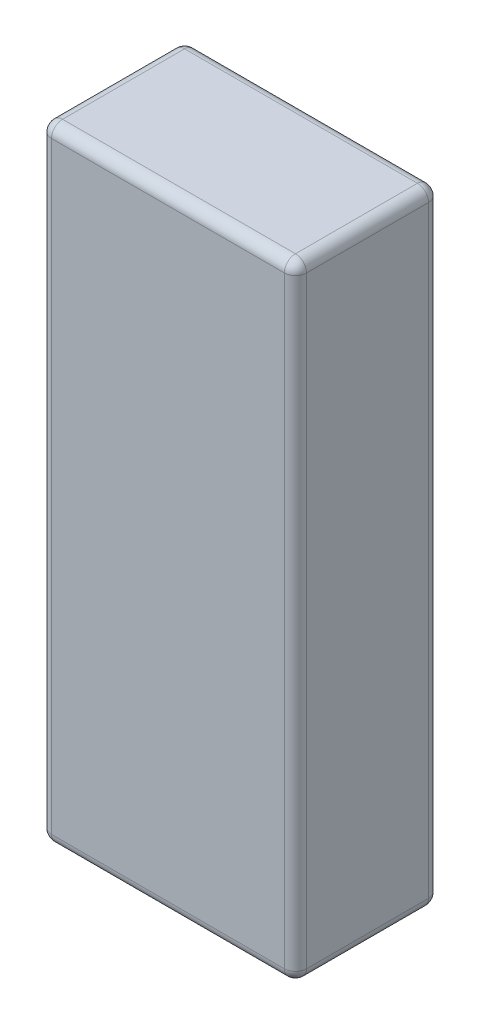
SolidWorks part; units mm, degrees
ref_plane "Front Plane" through (0, 0, 0) normal (0, 0, 1) x (1, 0, 0)
ref_plane "Top Plane" through (0, 0, 0) normal (0, 1, 0) x (1, 0, 0)
ref_plane "Right Plane" through (0, 0, 0) normal (1, 0, 0) x (0, 0, -1)
sketch "Sketch1" plane through (0, 0, 0) normal (0, 0, 1) x (1, 0, 0)
  line L1 (-34.5, -84.5) -> (34.5, -84.5)
  line L2 (-34.5, -84.5) -> (-34.5, 84.5)
  line L3 (-34.5, 84.5) -> (34.5, 84.5)
  line L4 (34.5, -84.5) -> (34.5, 84.5)
  line L5 (-34.5, -84.5) -> (34.5, 84.5) construction
  line L6 (-34.5, 84.5) -> (34.5, -84.5) construction
  point P0 (0, 0)
  dimension "D1" = 69
  dimension "D2" = 169
extrude "Boss-Extrude1" add sketch "Sketch1" along normal mid plane 39
fillet "Fillet1" radius 3 12 edges at (-34.5, 0, 19.5) (-34.5, 0, -19.5) (34.5, 0, 19.5) (34.5, 0, -19.5) (-34.5, -84.5, 0) (0, -84.5, 19.5) (34.5, -84.5, 0) (0, -84.5, -19.5) (34.5, 84.5, 0) (0, 84.5, 19.5) (-34.5, 84.5, 0) (0, 84.5, -19.5)
